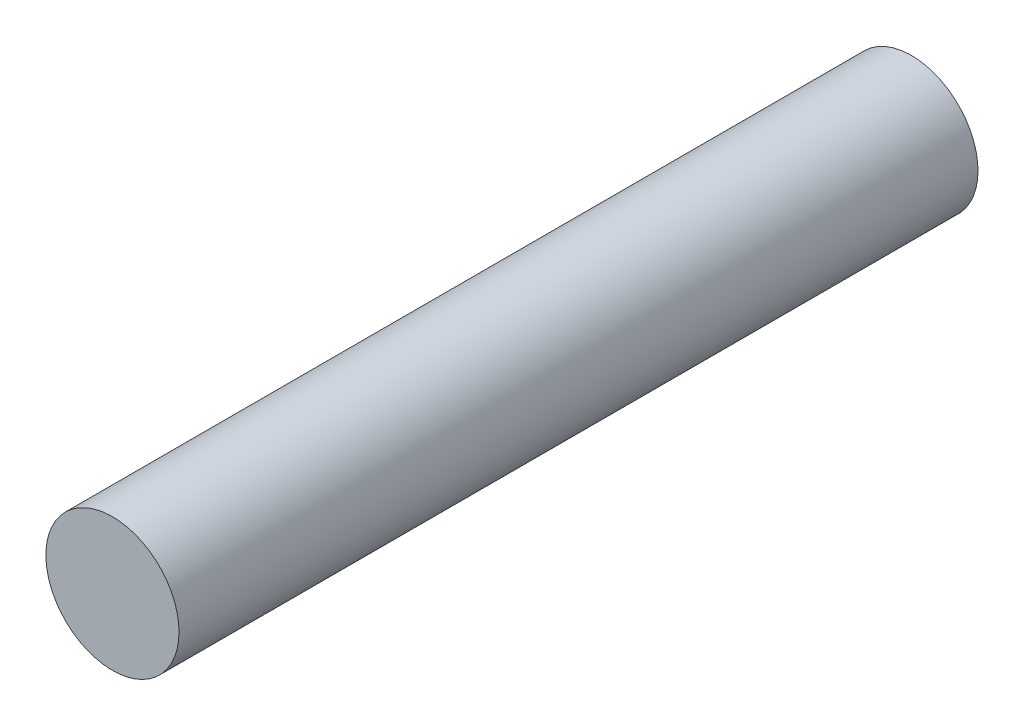
SolidWorks part; units mm, degrees
ref_plane "前视基准面" through (0, 0, 0) normal (0, 0, 1) x (1, 0, 0)
ref_plane "上视基准面" through (0, 0, 0) normal (0, 1, 0) x (1, 0, 0)
ref_plane "右视基准面" through (0, 0, 0) normal (1, 0, 0) x (0, 0, -1)
sketch "草图1" plane through (0, 0, 0) normal (0, 0, 1) x (1, 0, 0)
  circle A0 centre (0, 0) radius 1
  dimension "D1" = 2
extrude "凸台-拉伸1" add sketch "草图1" along normal blind 12
